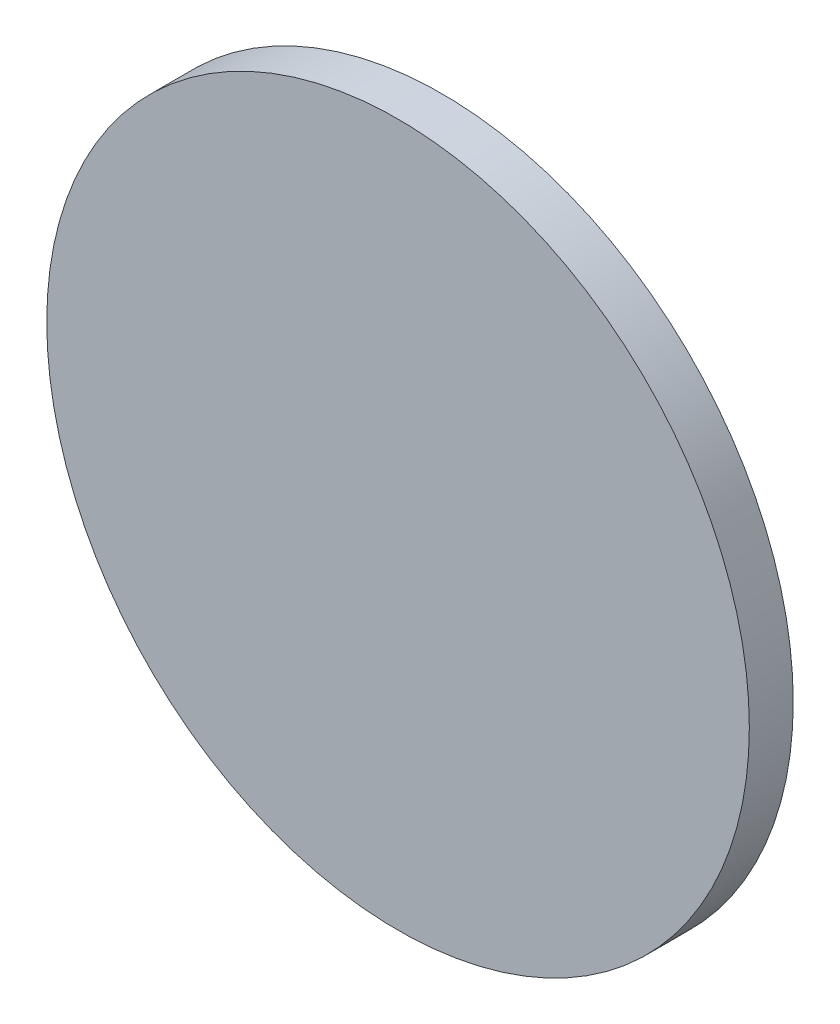
SolidWorks part; units mm, degrees
material "Silicon"
ref_plane "Front Plane" through (0, 0, 0) normal (0, 0, 1) x (1, 0, 0)
ref_plane "Top Plane" through (0, 0, 0) normal (0, 1, 0) x (1, 0, 0)
ref_plane "Right Plane" through (0, 0, 0) normal (1, 0, 0) x (0, 0, -1)
sketch "Sketch1" plane through (0, 0, 0) normal (0, 0, 1) x (1, 0, 0)
  circle A0 centre (0, 0) radius 4
  dimension "D1" = 8
extrude "Boss-Extrude1" add sketch "Sketch1" against normal blind 0.5
